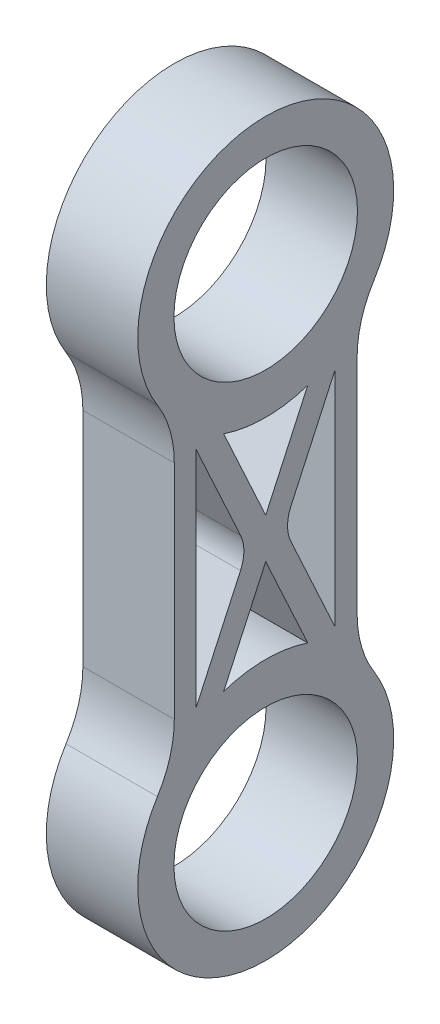
SolidWorks part; units mm, degrees
ref_plane "Front Plane" through (0, 0, 0) normal (0, 0, 1) x (1, 0, 0)
ref_plane "Top Plane" through (0, 0, 0) normal (0, 1, 0) x (1, 0, 0)
ref_plane "Right Plane" through (0, 0, 0) normal (1, 0, 0) x (0, 0, -1)
sketch "Sketch3" plane through (0, 0, 0) normal (1, 0, 0) x (0, 0, -1)
  line L0 (-35.9952, 38.6703) -> (-35.9952, 25.6703)
  line L1 (-30.9952, 38.6703) -> (-30.9952, 25.6703)
  arc A0 (-35.9952, 38.6703) -> (-30.9952, 38.6703) centre (-33.4952, 38.6703) cw
  arc A1 (-30.9952, 25.6703) -> (-35.9952, 25.6703) centre (-33.4952, 25.6703) cw
  dimension "D1" = 13
  dimension "D2" = 5
extrude "Boss-Extrude3" add sketch "Sketch3" along normal blind 2.5
sketch "Sketch4" plane through (2.5, 0, 0) normal (1, 0, 0) x (0, 0, -1)
  circle A0 centre (-33.4952, 38.6703) radius 3.5
  circle A1 centre (-33.4952, 25.6703) radius 3.5
  dimension "D1" = 7
  dimension "D2" = 7
extrude "Boss-Extrude4" add sketch "Sketch4" against normal blind 2.5
sketch "Sketch5" plane through (2.5, 0, 0) normal (1, 0, 0) x (0, 0, -1)
  circle A0 centre (-33.4952, 38.6703) radius 2.51
  circle A1 centre (-33.4952, 25.6703) radius 2.51
  dimension "D1" = 5.02
  dimension "D2" = 5.02
extrude "Cut-Extrude1" cut sketch "Sketch5" against normal blind 2.5
sketch "Sketch8" plane through (2.5, 0, 0) normal (1, 0, 0) x (0, 0, -1)
  line L0 (-35.3952, 35.2208) -> (-35.3952, 29.1198)
  line L1 (-35.3952, 29.1198) -> (-33.992, 32.1703)
  line L2 (-33.992, 32.1703) -> (-35.3952, 35.2208)
  line L3 (-31.5952, 35.2208) -> (-31.5952, 29.1198)
  line L4 (-31.5952, 29.1198) -> (-32.9985, 32.1703)
  line L5 (-32.9985, 32.1703) -> (-31.5952, 35.2208)
  line L6 (-34.6452, 35.2208) -> (-33.4952, 32.7208)
  line L7 (-33.4952, 32.7208) -> (-32.3452, 35.2208)
  line L8 (-33.4952, 31.6198) -> (-32.3452, 29.1198)
  line L9 (-33.4952, 31.6198) -> (-34.6452, 29.1198)
  line L10 (-35.9952, 36.2208) -> (-35.9952, 28.1198) construction
  line L11 (-30.9952, 28.1198) -> (-30.9952, 36.2208) construction
  arc A0 (-34.6452, 35.2208) -> (-32.3452, 35.2208) centre (-33.4952, 38.6703) ccw
  arc A1 (-34.6452, 29.1198) -> (-32.3452, 29.1198) centre (-33.4952, 25.6703) cw
  point P16 (-32.2465, 29.0127)
  dimension "D1" = 1.35
  dimension "D2" = 1.35
  dimension "D3" = 1
  dimension "D4" = 2.5
  dimension "D5" = 3.5
  dimension "D6" = 3.5
  dimension "D7" = 1.35
  dimension "D8" = 1.35
  dimension "D9" = 2.5
  dimension "D10" = 0.6
  dimension "D11" = 0.6
  dimension "D12" = 1
  dimension "D13" = 1
  dimension "D14" = 1
  dimension "D15" = 1
  dimension "D16" = 1
extrude "Cut-Extrude2" cut sketch "Sketch8" against normal blind 2.5
fillet "Fillet2" radius 3 4 edges at (1.25, 36.2208, 35.9952) (1.25, 36.2208, 30.9952) (1.25, 28.1198, 30.9952) (1.25, 28.1198, 35.9952)
fillet "Fillet3" radius 1 2 edges at (1.25, 32.1703, 33.992) (1.25, 32.1703, 32.9985)
